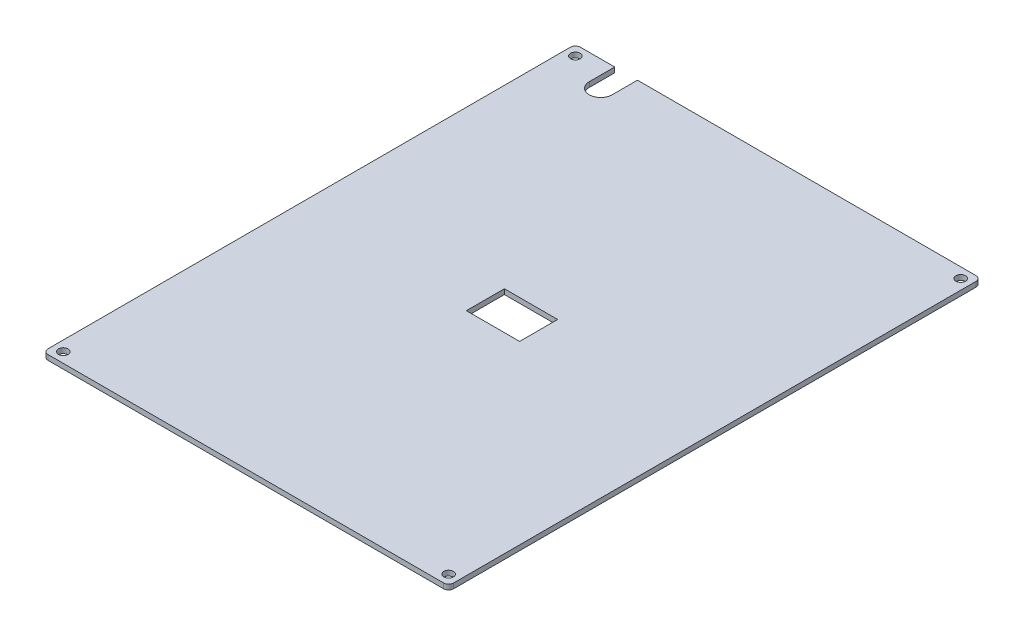
SolidWorks part; units mm, degrees
ref_plane "Front Plane" through (0, 0, 0) normal (0, 0, 1) x (1, 0, 0)
ref_plane "Top Plane" through (0, 0, 0) normal (0, 1, 0) x (1, 0, 0)
ref_plane "Right Plane" through (0, 0, 0) normal (1, 0, 0) x (0, 0, -1)
sketch "Sketch1" plane through (0, 0, 0) normal (0, 1, 0) x (1, 0, 0)
  line L1 (0, 0) -> (160, 0)
  line L2 (0, 0) -> (0, 210)
  line L3 (0, 210) -> (160, 210)
  line L4 (160, 0) -> (160, 210)
  dimension "D1" = 160
  dimension "D2" = 210
extrude "Boss-Extrude1" add sketch "Sketch1" along normal blind 2
sketch "Sketch2" plane through (0, 2, 0) normal (0, 1, 0) x (1, 0, 0)
  line L0 (4, 210) -> (4, 206) construction
  line L1 (160, 210) -> (0, 210) construction
  line L2 (4, 206) -> (0, 206) construction
  line L3 (0, 210) -> (0, 0) construction
  line L4 (80, 210) -> (80, 0) construction
  line L5 (0, 0) -> (160, 0) construction
  line L6 (0, 105) -> (160, 105) construction
  line L7 (160, 0) -> (160, 210) construction
  line L8 (156, 206) -> (160, 206) construction
  line L9 (156, 210) -> (156, 206) construction
  line L10 (156, 0) -> (156, 4) construction
  line L11 (156, 4) -> (160, 4) construction
  line L12 (4, 4) -> (0, 4) construction
  line L13 (4, 0) -> (4, 4) construction
  line L14 (150, 10) -> (150, 0) construction
  line L15 (150, 10) -> (160, 10) construction
  line L16 (0, 200) -> (20, 200) construction
  line L17 (20, 200) -> (20, 210) construction
  line L18 (24.5, 200) -> (24.5, 210)
  line L19 (15.5, 200) -> (15.5, 210)
  line L20 (15.5, 210) -> (24.5, 210)
  circle A0 centre (4, 206) radius 1.9
  circle A1 centre (156, 206) radius 1.9
  circle A2 centre (156, 4) radius 1.9
  circle A3 centre (4, 4) radius 1.9
  arc A5 (15.5, 200) -> (24.5, 200) centre (20, 200) ccw
  dimension "D2" = 3.8
  dimension "D8" = 9
  dimension "D1" = 4
  dimension "D3" = 10
  dimension "D4" = 10
  dimension "D6" = 10
  dimension "D7" = 20
extrude "Cut-Extrude1" cut sketch "Sketch2" against normal blind 10
fillet "Fillet1" radius 2 4 edges at (0, 1, 0) (160, 1, 0) (160, 1, -210) (0, 1, -210)
sketch "Sketch3" plane through (0, 2, 0) normal (0, 1, 0) x (1, 0, 0)
  line L0 (0, 105) -> (80, 105) construction
  line L1 (0, 208) -> (0, 2) construction
  line L3 (69.5, 97.5) -> (90.5, 97.5)
  line L4 (69.5, 97.5) -> (69.5, 112.5)
  line L5 (69.5, 112.5) -> (90.5, 112.5)
  line L6 (90.5, 97.5) -> (90.5, 112.5)
  line L7 (69.5, 97.5) -> (90.5, 112.5) construction
  line L8 (69.5, 112.5) -> (90.5, 97.5) construction
  dimension "D1" = 80
  dimension "D2" = 21
  dimension "D3" = 15
extrude "Cut-Extrude2" cut sketch "Sketch3" against normal blind 10
